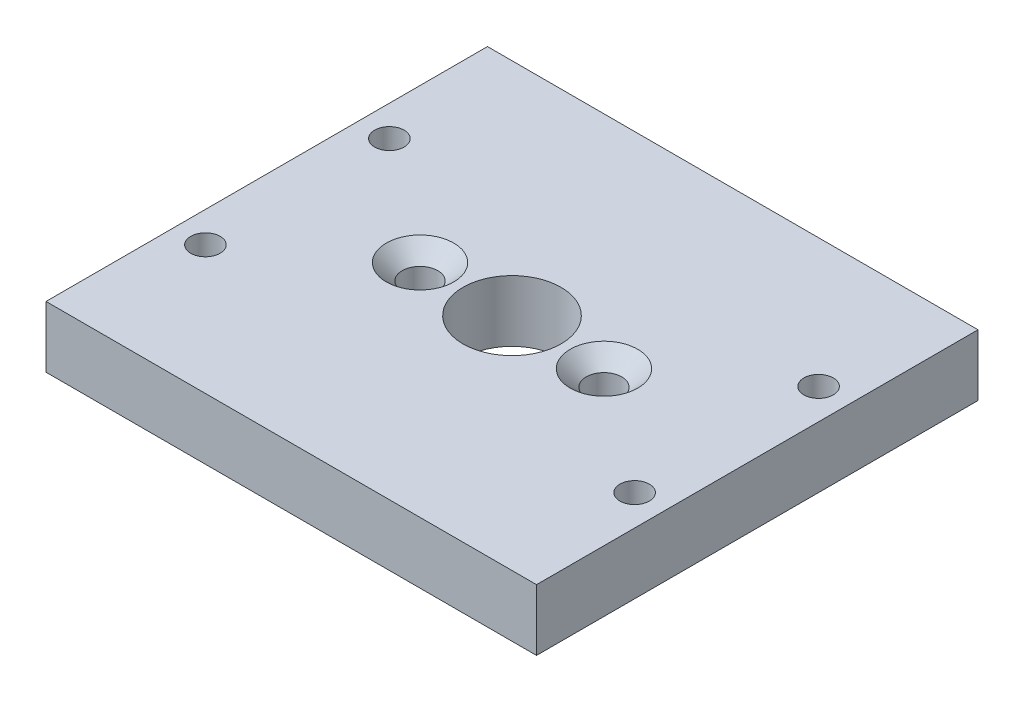
SolidWorks part; units mm, degrees
ref_plane "Front Plane" through (0, 0, 0) normal (0, 0, 1) x (1, 0, 0)
ref_plane "Top Plane" through (0, 0, 0) normal (0, 1, 0) x (1, 0, 0)
ref_plane "Right Plane" through (0, 0, 0) normal (1, 0, 0) x (0, 0, -1)
sketch "Sketch1" plane through (0, 0, 0) normal (0, 1, 0) x (1, 0, 0)
  line L1 (20, -18) -> (-20, -18)
  line L2 (20, -18) -> (20, 18)
  line L3 (20, 18) -> (-20, 18)
  line L4 (-20, -18) -> (-20, 18)
  line L5 (20, -18) -> (-20, 18) construction
  line L6 (20, 18) -> (-20, -18) construction
  point P0 (0, 0)
  dimension "D1" = 40
  dimension "D2" = 36
extrude "Boss-Extrude1" add sketch "Sketch1" along normal blind 5
sketch "Sketch2" plane through (0, 5, 0) normal (0, 1, 0) x (1, 0, 0)
  circle A0 centre (0, 0) radius 4
extrude "Cut-Extrude1" cut sketch "Sketch2" against normal through all
sketch "Sketch3" plane through (0, 5, 0) normal (0, 1, 0) x (1, 0, 0)
  line L0 (0, 0) -> (0, 7.5) construction
  line L1 (0, 0) -> (4, 0) construction
  line L2 (-15, -18) -> (-15, 18) construction
  line L3 (-20, -18) -> (20, -18) construction
  line L4 (20, 18) -> (-20, 18) construction
  line L5 (15, -18) -> (15, 18) construction
  line L6 (-20, -7.5) -> (20, -7.5) construction
  line L7 (-20, 18) -> (-20, -18) construction
  line L8 (20, -18) -> (20, 18) construction
  line L9 (-20, 7.5) -> (20, 7.5) construction
  line L10 (-17.5, -12.2117) -> (-17.5, 15.0755) construction
  line L11 (17.5, -11.2391) -> (17.5, 15.0755) construction
  line L12 (7.5, 7.5) -> (7.5, -7.5) construction
  line L13 (-7.5, 10.2308) -> (-7.5, -4.1711) construction
  line L14 (-8.812, 0) -> (9.0391, 0) construction
  circle A0 centre (0, 0) radius 4 construction
  point P3 (0, 7.5)
  point P4 (0, -7.5)
  dimension "D1" = 7.5
  dimension "D2" = 15
  dimension "D3" = 30
  dimension "D4" = 2.5
  dimension "D5" = 2.5
  dimension "D6" = 7.5
  dimension "D7" = 7.5
  dimension "D8" = 7.5
hole_wizard "CSK for M2.5 Countersunk Flat Head Screw1" positions "Sketch4" profile "Sketch5" countersink size "M2.5" standard "ISO" end condition up to next
sketch "Sketch4" plane through (0, 5, 0) normal (0, 1, 0) x (1, 0, 0)
  line L0 (-7.5, 10.2308) -> (-7.5, -4.1711) construction
  line L1 (7.5, 7.5) -> (7.5, -7.5) construction
  line L2 (-8.812, 0) -> (9.0391, 0) construction
  point P10 (-7.5, 0)
  point P14 (7.5, 0)
sketch "Sketch5" plane through (-7.5, 5, 0) normal (1, 0, 0) x (0, 0, 1)
  line L0 (0, 0) -> (0, 5)
  line L1 (0, 5) -> (1.45, 5)
  line L2 (1.45, 5) -> (1.45, 1.3)
  line L3 (1.45, 1.3) -> (2.75, 0)
  line L5 (2.75, 0) -> (0, 0)
  line L6 (-1.45, 1.3) -> (-2.75, 0) construction
  line L11 (0, -6.35) -> (0, 107.95) construction
  dimension "Thru Hole Dia." = 2.9
  dimension "Thru Hole Depth" = 5
  dimension "Near C'Sink Dia." = 5.5
  dimension "Near C'Sink Angle" = 90
hole_wizard "CSK for M2 Countersunk Flat Head Screw1" positions "Sketch6" profile "Sketch7" countersink size "M2" standard "ISO" end condition up to next
sketch "Sketch6" plane through (0, 0, 0) normal (0, -1, 0) x (-1, 0, 0)
  line L0 (20, -7.5) -> (-20, -7.5) construction
  line L1 (17.5, -12.2117) -> (17.5, 15.0755) construction
  line L2 (20, 7.5) -> (-20, 7.5) construction
  line L3 (-17.5, -11.2391) -> (-17.5, 15.0755) construction
  point P0 (17.5, -7.5)
  point P6 (17.5, 7.5)
  point P10 (-17.5, 7.5)
  point P14 (-17.5, -7.5)
sketch "Sketch7" plane through (-17.5, 0, 7.5) normal (1, 0, 0) x (0, 0, -1)
  line L0 (0, 0) -> (0, 5)
  line L1 (0, 5) -> (1.2, 5)
  line L2 (1.2, 5) -> (1.2, 1)
  line L3 (1.2, 1) -> (2.2, 0)
  line L5 (2.2, 0) -> (0, 0)
  line L6 (-1.2, 1) -> (-2.2, 0) construction
  line L11 (0, -6.35) -> (0, 107.95) construction
  dimension "Thru Hole Dia." = 2.4
  dimension "Thru Hole Depth" = 5
  dimension "Near C'Sink Dia." = 4.4
  dimension "Near C'Sink Angle" = 90
